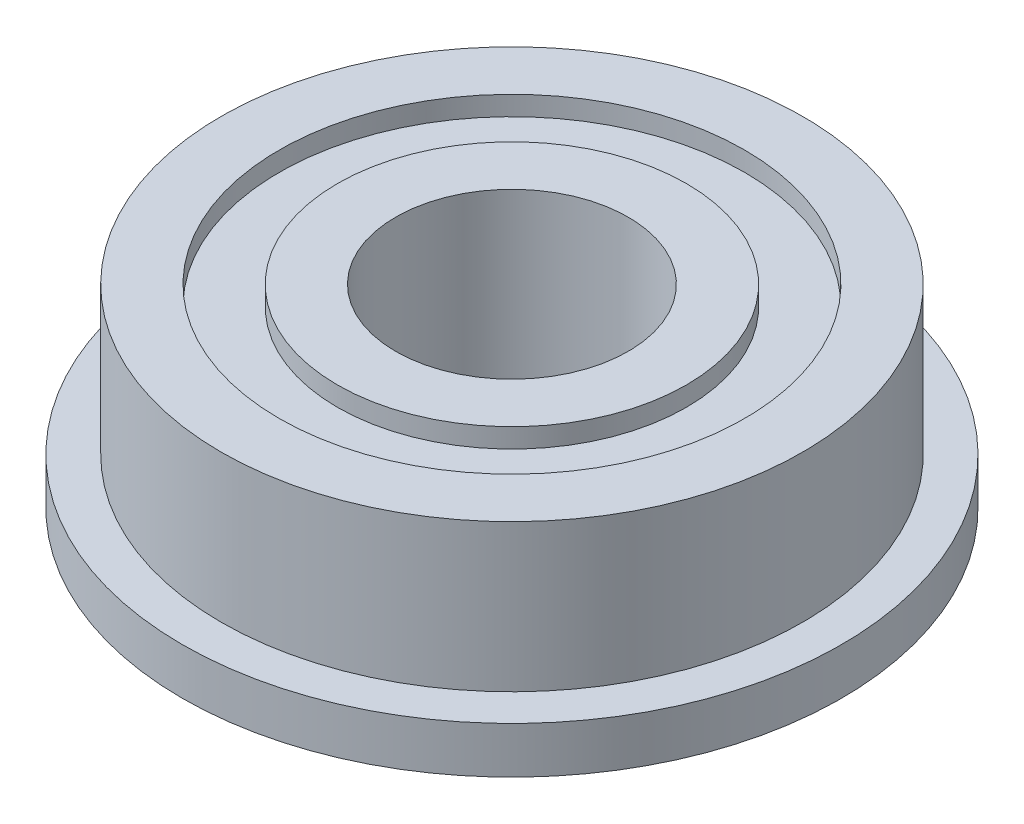
SolidWorks part; units mm, degrees
material "合金钢"
ref_plane "前视基准面" through (0, 0, 0) normal (0, 0, 1) x (1, 0, 0)
ref_plane "上视基准面" through (0, 0, 0) normal (0, 1, 0) x (1, 0, 0)
ref_plane "右视基准面" through (0, 0, 0) normal (1, 0, 0) x (0, 0, -1)
other "Configuration Table"
sketch "草图1" plane through (0, 0, 0) normal (0, 0, 1) x (1, 0, 0)
  line L0 (0, 7.2094) -> (0, -7.1767) construction
  line L1 (3, 0) -> (3, 5)
  line L2 (3, 5) -> (4.5, 5)
  line L3 (4.5, 5) -> (4.5, 4.5)
  line L4 (4.5, 4.5) -> (6, 4.5)
  line L5 (6, 4.5) -> (6, 5)
  line L6 (6, 5) -> (7.5, 5)
  line L7 (7.5, 5) -> (7.5, 1.2)
  line L8 (7.5, 1.2) -> (8.5, 1.2)
  line L9 (8.5, 1.2) -> (8.5, 0)
  line L10 (8.5, 0) -> (6, 0)
  line L11 (6, 0) -> (6, 0.5)
  line L12 (6, 0.5) -> (4.5, 0.5)
  line L13 (4.5, 0.5) -> (4.5, 0)
  line L14 (4.5, 0) -> (3, 0)
  point P5 (8.5, 0.6)
  point P18 (6, 0.25)
  dimension "D1" = 3
  dimension "D2" = 7.5
  dimension "D3" = 5
  dimension "D4" = 8.5
  dimension "D5" = 1.2
  dimension "D6" = 0.5
  dimension "D7" = 0.5
  dimension "D8" = 1.5
  dimension "D10" = 1.5
  dimension "D11" = 1.5
revolve "旋转1" add sketch "草图1" angle 360 about L0
